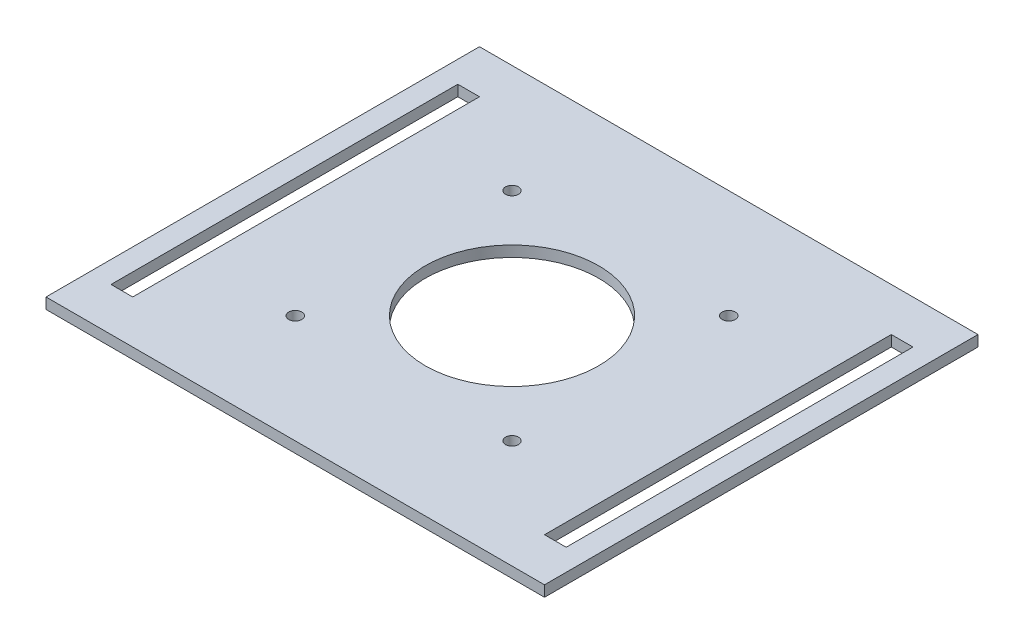
SolidWorks part; units mm, degrees
ref_plane "Front Plane" through (0, 0, 0) normal (0, 0, 1) x (1, 0, 0)
ref_plane "Top Plane" through (0, 0, 0) normal (0, 1, 0) x (1, 0, 0)
ref_plane "Right Plane" through (0, 0, 0) normal (1, 0, 0) x (0, 0, -1)
sketch "Sketch1" plane through (0, 0, 0) normal (0, 1, 0) x (1, 0, 0)
  line L0 (0, 100) -> (0, -100) construction
  line L1 (-115, 100) -> (115, 100)
  line L2 (-115, 100) -> (-115, -100)
  line L3 (-115, -100) -> (115, -100)
  line L4 (115, 100) -> (115, -100)
  line L5 (-115, 100) -> (115, -100) construction
  line L6 (-115, -100) -> (115, 100) construction
  line L7 (-105, 80) -> (-95, 80)
  line L8 (-105, 80) -> (-105, -80)
  line L9 (-105, -80) -> (-95, -80)
  line L10 (-95, 80) -> (-95, -80)
  line L11 (105, -80) -> (95, -80)
  line L12 (95, 80) -> (95, -80)
  line L13 (105, 80) -> (95, 80)
  line L14 (105, 80) -> (105, -80)
  point P0 (0, 0)
  point P11 (-95, 0)
  dimension "D1" = 230
  dimension "D2" = 200
  dimension "D3" = 95
  dimension "D4" = 10
  dimension "D5" = 160
extrude "Boss-Extrude1" add sketch "Sketch1" along normal blind 5 contours L4 L1 L2 L3 L7 L10 L9 L8 L13 L14 L11 L12
sketch "Sketch2" plane through (0, 5, 0) normal (0, 1, 0) x (1, 0, 0)
  line L1 (-50, 50) -> (50, 50) construction
  line L2 (-50, 50) -> (-50, -50) construction
  line L3 (-50, -50) -> (50, -50) construction
  line L4 (50, 50) -> (50, -50) construction
  line L5 (-50, 50) -> (50, -50) construction
  line L6 (-50, -50) -> (50, 50) construction
  circle A0 centre (0, 0) radius 40
  circle A1 centre (-50, 50) radius 3
  circle A2 centre (50, 50) radius 3
  circle A3 centre (50, -50) radius 3
  circle A4 centre (-50, -50) radius 3
  dimension "D1" = 80
  dimension "D4" = 6
  dimension "D2" = 100
  dimension "D3" = 100
extrude "Cut-Extrude1" cut sketch "Sketch2" against normal up to surface (5 mm away) up to face at (0, 0, 0)
